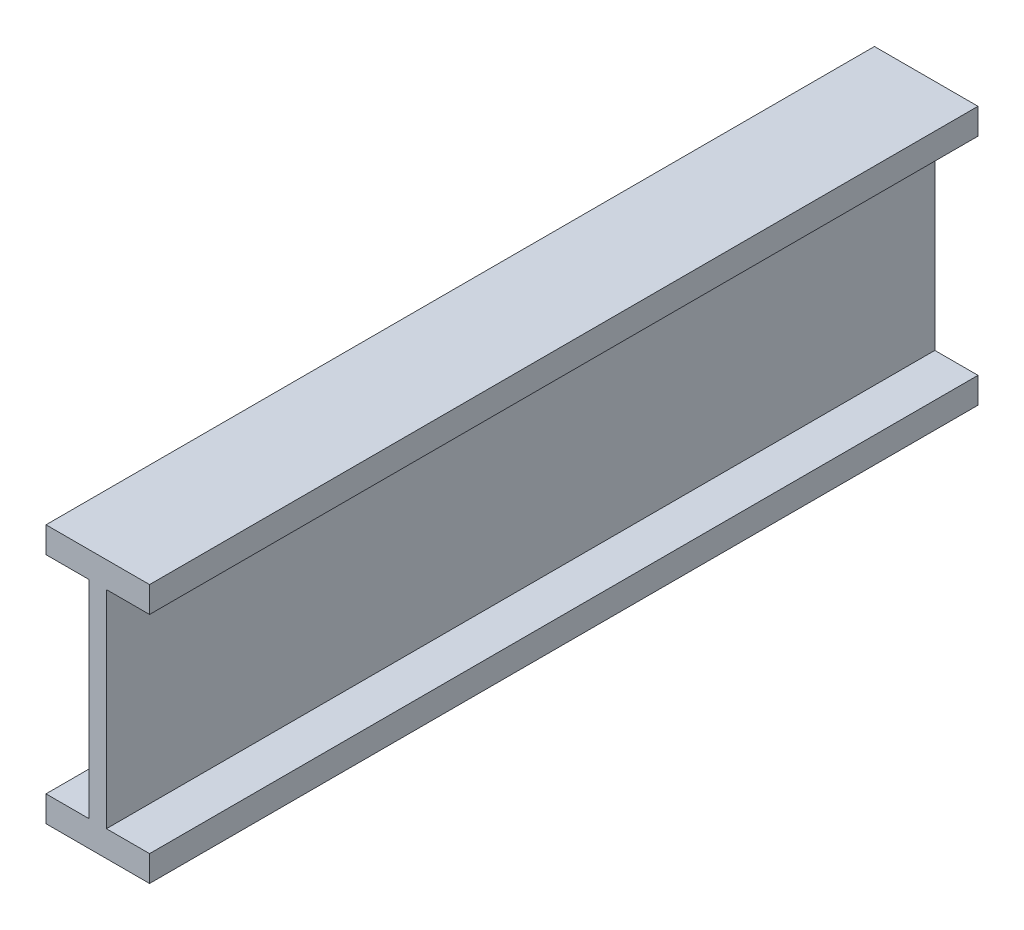
SolidWorks part; units mm, degrees
material "Oak"
ref_plane "Front Plane" through (0, 0, 0) normal (0, 0, 1) x (1, 0, 0)
ref_plane "Top Plane" through (0, 0, 0) normal (0, 1, 0) x (1, 0, 0)
ref_plane "Right Plane" through (0, 0, 0) normal (1, 0, 0) x (0, 0, -1)
sketch "Sketch2" plane through (0, 0, 0) normal (0, 0, 1) x (1, 0, 0)
  line L1 (-12.7, -152.4) -> (12.7, -152.4)
  line L2 (-12.7, -152.4) -> (-12.7, 152.4)
  line L3 (-12.7, 152.4) -> (12.7, 152.4)
  line L4 (12.7, -152.4) -> (12.7, 152.4)
  line L5 (-12.7, -152.4) -> (12.7, 152.4) construction
  line L6 (-12.7, 152.4) -> (12.7, -152.4) construction
  line L7 (-76.2, 190.5) -> (76.2, 190.5)
  line L8 (-76.2, 190.5) -> (-76.2, 152.4)
  line L9 (-76.2, 152.4) -> (76.2, 152.4)
  line L10 (76.2, 190.5) -> (76.2, 152.4)
  line L11 (-76.2, 190.5) -> (76.2, 152.4) construction
  line L12 (-76.2, 152.4) -> (76.2, 190.5) construction
  line L13 (-76.2, -190.5) -> (76.2, -190.5)
  line L14 (-76.2, -190.5) -> (-76.2, -152.4)
  line L15 (-76.2, -152.4) -> (76.2, -152.4)
  line L16 (76.2, -190.5) -> (76.2, -152.4)
  line L17 (-76.2, -190.5) -> (76.2, -152.4) construction
  line L18 (-76.2, -152.4) -> (76.2, -190.5) construction
  point P0 (0, 0)
  point P6 (0, 171.45)
  point P12 (0, -171.45)
  point P18 (0, -152.4)
  dimension "D1" = 304.8
  dimension "D2" = 25.4
  dimension "D3" = 38.1
  dimension "D4" = 152.4
  dimension "D5" = 152.4
  dimension "D6" = 38.1
extrude "Boss-Extrude1" add sketch "Sketch2" along normal blind 1219.2 contours L10 L7 L8 L9 L3 | L1 L4 L3 L2 | L13 L16 L15 L1 L14
